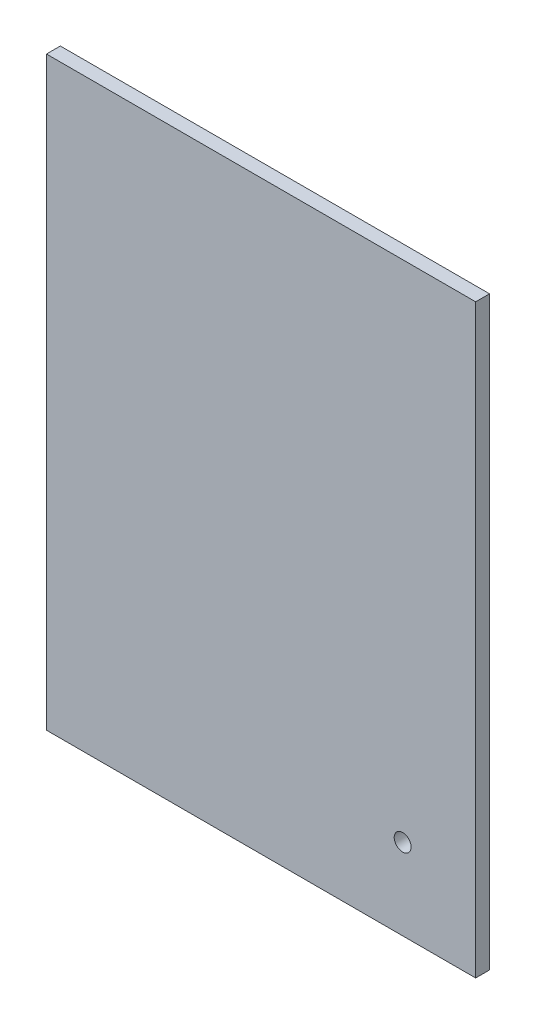
SolidWorks part; units mm, degrees
material "Sosna"
ref_plane "Płaszczyzna przednia" through (0, 0, 0) normal (0, 0, 1) x (1, 0, 0)
ref_plane "Płaszczyzna górna" through (0, 0, 0) normal (0, 1, 0) x (1, 0, 0)
ref_plane "Płaszczyzna prawa" through (0, 0, 0) normal (1, 0, 0) x (0, 0, -1)
sketch "Szkic1" plane through (0, 0, 0) normal (0, 0, 1) x (1, 0, 0)
  line L1 (0, 760) -> (557, 760)
  line L2 (0, 760) -> (0, 0)
  line L3 (0, 0) -> (557, 0)
  line L4 (557, 760) -> (557, 0)
  dimension "D1" = 760
  dimension "D2" = 557
extrude "Dodanie-wyciągnięcie1" add sketch "Szkic1" along normal blind 18 contours L2 L3 L4 L1
sketch "Szkic2" plane through (0, 0, 18) normal (0, 0, 1) x (1, 0, 0)
  circle A0 centre (462.2542, 105.1915) radius 10.9704
extrude "Wytnij-wyciągnięcie1" cut sketch "Szkic2" against normal up to next
